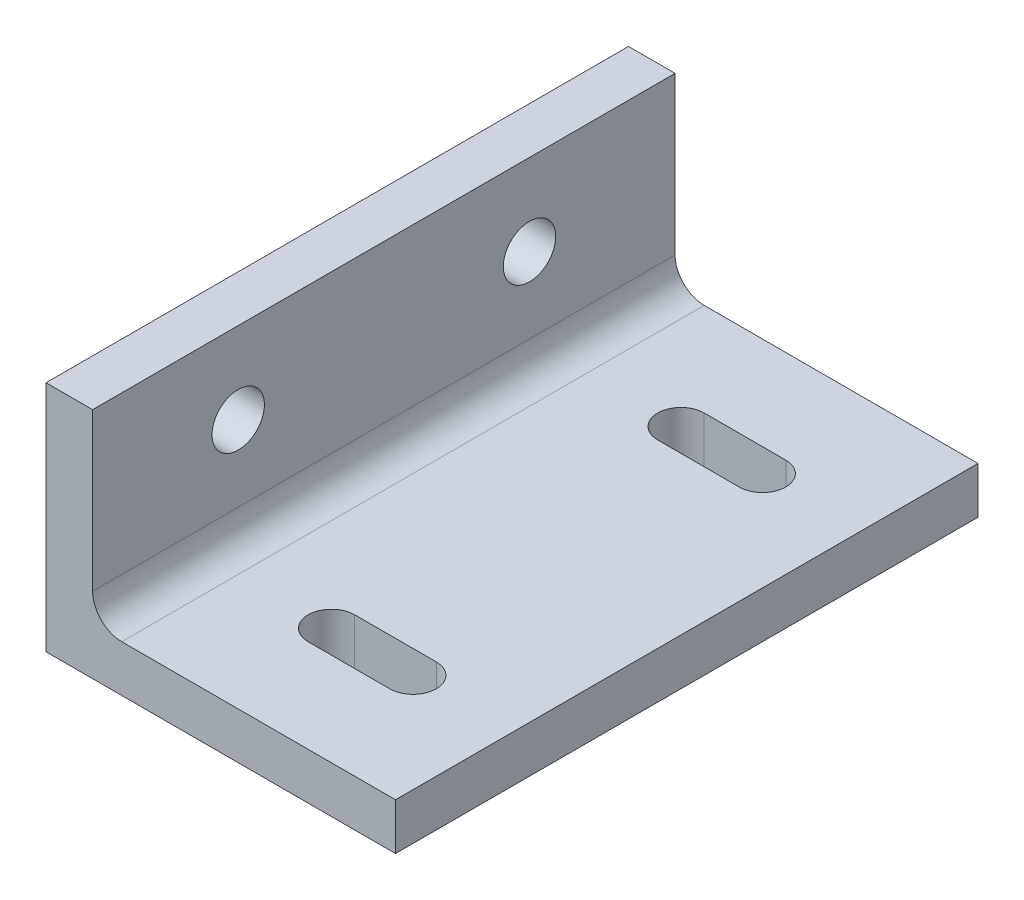
SolidWorks part; units mm, degrees
ref_plane "前视基准面" through (0, 0, 0) normal (0, 0, 1) x (1, 0, 0)
ref_plane "上视基准面" through (0, 0, 0) normal (0, 1, 0) x (1, 0, 0)
ref_plane "右视基准面" through (0, 0, 0) normal (1, 0, 0) x (0, 0, -1)
sketch "草图1" plane through (0, 0, 0) normal (0, 0, 1) x (1, 0, 0)
  line L0 (0, 0) -> (60, 0)
  line L1 (60, 0) -> (60, 8)
  line L2 (60, 8) -> (13, 8)
  line L3 (8, 13) -> (8, 40)
  line L4 (8, 40) -> (0, 40)
  line L5 (0, 40) -> (0, 0)
  arc A0 (13, 8) -> (8, 13) centre (13.0001, 13.0001) cw
extrude "凸台-拉伸1" add sketch "草图1" along normal blind 100
ref_plane "基准面1" through (0, 0, 40) normal (0, 0, 1) x (1, 0, 0)
ref_plane "基准面2" through (0, 8, 0) normal (0, 1, 0) x (1, 0, 0)
sketch "草图3" plane through (0, 8, 0) normal (0, 1, 0) x (1, 0, 0)
  line L0 (29, -16) -> (43, -16)
  line L1 (43, -24) -> (29, -24)
  line L2 (29, -76) -> (43, -76)
  line L3 (43, -84) -> (29, -84)
  arc A0 (43, -16) -> (43, -24) centre (43, -20) cw
  arc A1 (29, -24) -> (29, -16) centre (29, -20) cw
  arc A2 (43, -76) -> (43, -84) centre (43, -80) cw
  arc A3 (29, -84) -> (29, -76) centre (29, -80) cw
extrude "切除-拉伸3" cut sketch "草图3" against normal through all
sketch "草图4" plane through (0, 0, 0) normal (1, 0, 0) x (0, 0, -1)
  circle A0 centre (-25, 26) radius 4.5
  circle A1 centre (-75, 26) radius 4.5
extrude "切除-拉伸4" cut sketch "草图4" along normal through all
